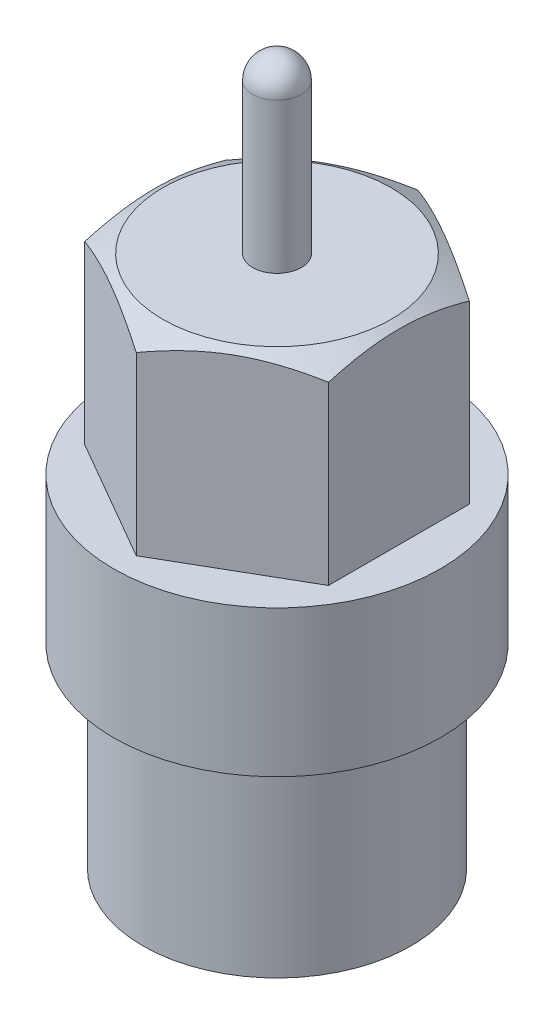
SolidWorks part; units mm, degrees
ref_plane "Face" through (0, 0, 0) normal (0, 0, 1) x (1, 0, 0)
ref_plane "Dessus" through (0, 0, 0) normal (0, 1, 0) x (1, 0, 0)
ref_plane "Droite" through (0, 0, 0) normal (1, 0, 0) x (0, 0, -1)
sketch "Esquisse1" plane through (0, 0, 0) normal (0, 0, 1) x (1, 0, 0)
  line L0 (0, 14.9688) -> (0, -4.6572) construction
  line L1 (-0.5312, 0) -> (-2.75, 0)
  line L2 (0, -0.8) -> (0, 14.5)
  line L3 (-2.3408, 10.9242) -> (-3, 10.5436)
  line L4 (-2.75, 0) -> (-2.75, 4)
  line L5 (-0.5312, 0) -> (0, -0.8)
  line L6 (-2.75, 4) -> (-3.3522, 4)
  line L8 (-3, 7) -> (-3.3522, 7)
  line L9 (-3.3522, 4) -> (-3.3522, 7)
  line L10 (-0.5, 14) -> (-0.5, 10.9242)
  line L11 (-0.5, 10.9242) -> (-2.3408, 10.9242)
  line L14 (-3, 10.5436) -> (-3, 7)
  arc A0 (0, 14.5) -> (-0.5, 14) centre (0, 14) ccw
  dimension "D3" = 1
  dimension "D1" = 30
  dimension "D2" = 4
  dimension "D4" = 10
  dimension "D5" = 0.8
  dimension "D7" = 3
revolve "Base-Révolution" add sketch "Esquisse1" angle 360 about L0
sketch "Esquisse2" plane through (0, 10.9242, 0) normal (0, 1, 0) x (-1, 0, 0)
  line L1 (0, 2.8868) -> (-2.5, 1.4434)
  line L2 (-2.5, 1.4434) -> (-2.5, -1.4434)
  line L3 (-2.5, -1.4434) -> (0, -2.8868)
  line L4 (0, -2.8868) -> (2.5, -1.4434)
  line L5 (2.5, -1.4434) -> (2.5, 1.4434)
  line L6 (2.5, 1.4434) -> (0, 2.8868)
  circle A0 centre (0, 0) radius 2.5 construction
  dimension "D1" = 5
extrude "Enlèv. mat.-Extru.1" cut sketch "Esquisse2" against normal up to surface (3.9242 mm away) flip side to cut up to face at (0, 7, 3.3522)
